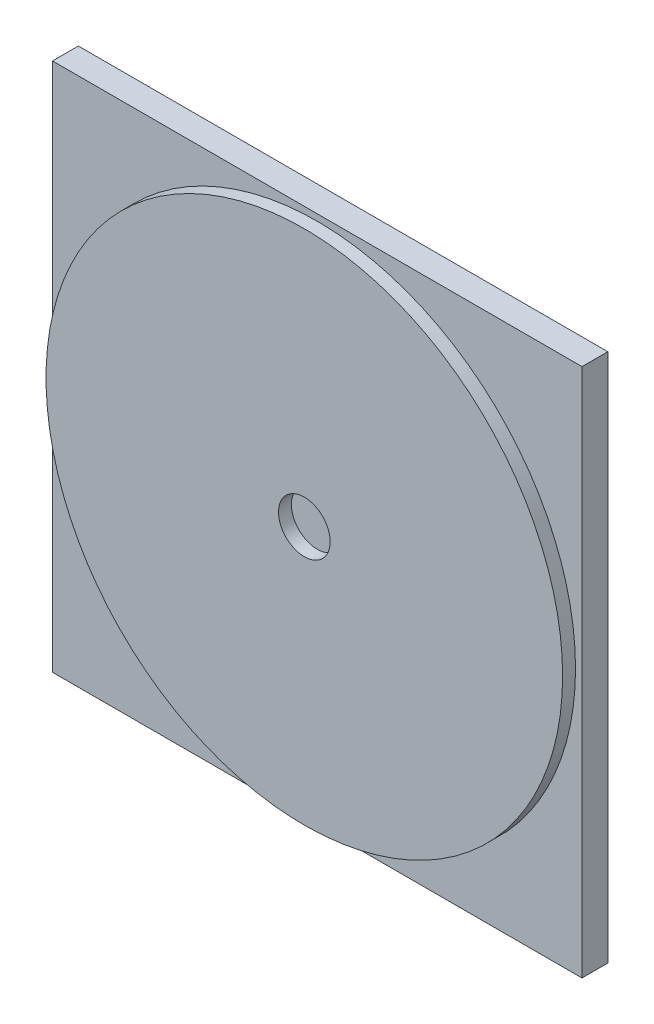
SolidWorks part; units mm, degrees
ref_plane "Front Plane" through (0, 0, 0) normal (0, 0, 1) x (1, 0, 0)
ref_plane "Top Plane" through (0, 0, 0) normal (0, 1, 0) x (1, 0, 0)
ref_plane "Right Plane" through (0, 0, 0) normal (1, 0, 0) x (0, 0, -1)
sketch "Sketch1" plane through (0, 0, 0) normal (0, 0, 1) x (1, 0, 0)
  line L1 (-22.0558, 11.8973) -> (18.9442, 11.8973)
  line L2 (-22.0558, 11.8973) -> (-22.0558, -29.1027)
  line L3 (-22.0558, -29.1027) -> (18.9442, -29.1027)
  line L4 (18.9442, 11.8973) -> (18.9442, -29.1027)
  dimension "D1" = 41
  dimension "D2" = 41
extrude "Boss-Extrude1" add sketch "Sketch1" along normal blind 2
sketch "Sketch2" plane through (0, 0, 2) normal (0, 0, 1) x (1, 0, 0)
  line L0 (18.9442, -29.1027) -> (18.9442, 11.8973) construction
  line L1 (-22.0558, -29.1027) -> (18.9442, -29.1027) construction
  circle A0 centre (-1.5558, -8.6027) radius 20
  dimension "D1" = 20.5
  dimension "D3" = 40
  dimension "D2" = 20.5
extrude "Boss-Extrude2" add sketch "Sketch2" along normal blind 1
sketch "Sketch3" plane through (0, 0, 3) normal (0, 0, 1) x (1, 0, 0)
  circle A0 centre (-1.5558, -8.6027) radius 2
  circle A1 centre (-1.5558, -8.6027) radius 20 construction
  dimension "D1" = 4
  dimension "D2" = 0
extrude "Cut-Extrude1" cut sketch "Sketch3" against normal blind 1
